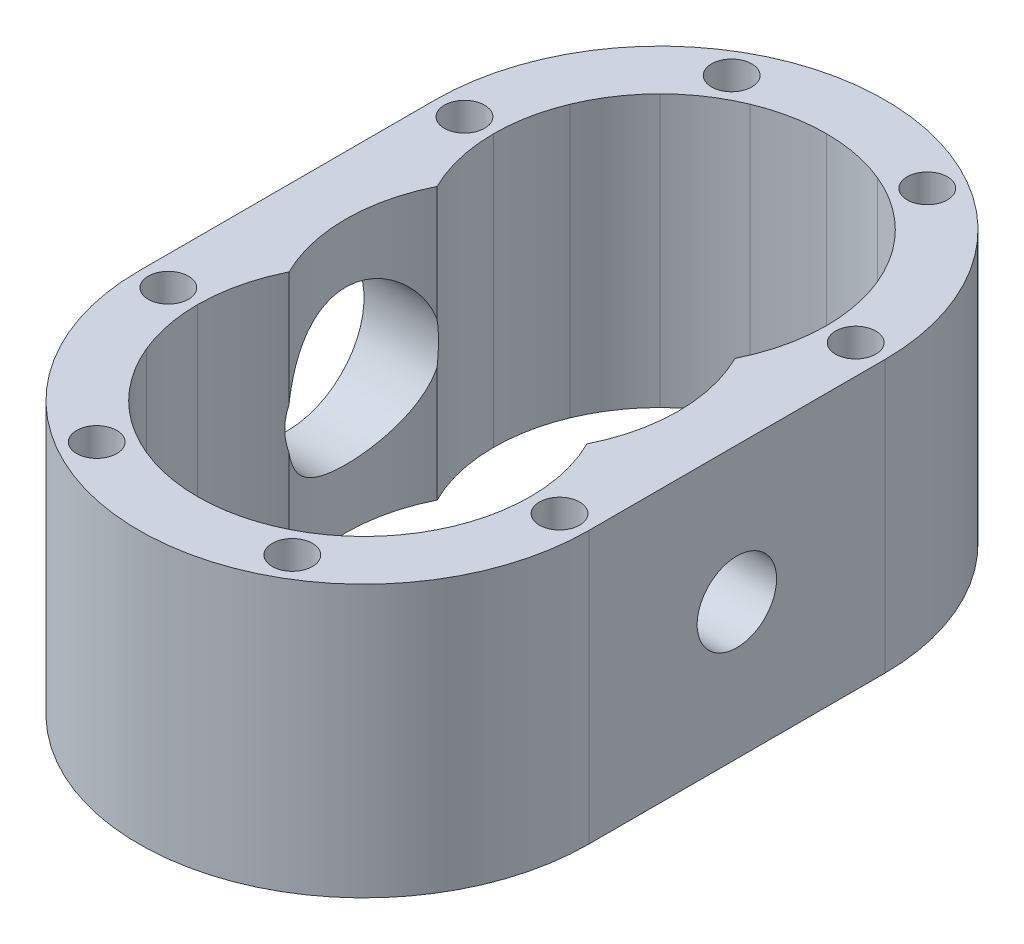
SolidWorks part; units mm, degrees
material "AISI 1020"
ref_plane "Ön Düzlem" through (0, 0, 0) normal (0, 0, 1) x (1, 0, 0)
ref_plane "Üst Düzlem" through (0, 0, 0) normal (0, 1, 0) x (1, 0, 0)
ref_plane "Sağ Düzlem" through (0, 0, 0) normal (1, 0, 0) x (0, 0, -1)
sketch "Çizim1" plane through (0, 0, 0) normal (0, 1, 0) x (1, 0, 0)
  line L0 (0, 40.5) -> (0, -40.5) construction
  line L1 (61.5, 40.5) -> (61.5, -40.5)
  line L2 (-61.5, 40.5) -> (-61.5, -40.5)
  arc A0 (61.5, 40.5) -> (-61.5, 40.5) centre (0, 40.5) ccw
  arc A1 (-61.5, -40.5) -> (61.5, -40.5) centre (0, -40.5) ccw
  point P3 (0, 0)
  dimension "D2" = 61.5
  dimension "D1" = 81
extrude "Yükseklik-Ekstrüzyon1" add sketch "Çizim1" along normal mid plane 74.3
sketch "Çizim2" plane through (0, 37.15, 0) normal (0, 1, 0) x (1, 0, 0)
  arc A0 (40.7454, 20.25) -> (-40.7454, 20.25) centre (0, 40.5) ccw
  arc A1 (-40.7454, -20.25) -> (40.7454, -20.25) centre (0, -40.5) ccw
  arc A2 (-40.7454, 20.25) -> (-40.7454, -20.25) centre (0, 0) ccw
  arc A3 (40.7454, -20.25) -> (40.7454, 20.25) centre (0, 0) ccw
  dimension "D1" = 91
extrude "Kes-Ekstrüzyon1" cut sketch "Çizim2" against normal up to surface (74.3 mm away) up to face at (0, -37.15, 0)
sketch "Çizim3" plane through (0, 37.15, 0) normal (0, 1, 0) x (1, 0, 0)
  line L0 (-45.5, 40.5) -> (-61.5, 40.5) construction
  line L1 (-61.5, 0) -> (61.5, 0) construction
  line L2 (-61.5, 40.5) -> (-61.5, -40.5) construction
  line L3 (61.5, -40.5) -> (61.5, 40.5) construction
  circle A0 centre (-53.5, 40.5) radius 5.5
  arc A1 (40.7454, 20.25) -> (-40.7454, 20.25) centre (0, 40.5) ccw construction
  dimension "D1" = 11
extrude "Kes-Ekstrüzyon2" cut sketch "Çizim3" against normal blind 12
pattern_circular "Dairesel Kaplama1" count 5 every 60 about axis through (0, 0, -40.5) along (0, 1, 0) of "Kes-Ekstrüzyon2"
mirror "Aynalama1" about plane through (0, 0, 0) normal (0, 0, 1) of "Dairesel Kaplama1", "Kes-Ekstrüzyon2"
mirror "Aynalama2" about plane through (0, 0, 0) normal (0, 1, 0) of "Dairesel Kaplama1", "Aynalama1", "Kes-Ekstrüzyon2"
sketch "Çizim4" plane through (-61.5, 0, 0) normal (-1, 0, 0) x (0, 0, 1)
  circle A0 centre (0, 0) radius 21.03
  dimension "D1" = 42.06
extrude "Kes-Ekstrüzyon3" cut sketch "Çizim4" against normal up to surface (21.1517 mm away)
sketch "Çizim5" plane through (61.5, 0, 0) normal (1, 0, 0) x (0, 0, -1)
  circle A0 centre (0, 0) radius 10.86
  dimension "D1" = 21.72
extrude "Kes-Ekstrüzyon4" cut sketch "Çizim5" against normal up to surface (17.315 mm away)
sketch "Çizim7" plane through (0, 0, 0) normal (1, 0, 0) x (0, 0, -1)
  line L0 (40.5, 37.15) -> (40.5, -37.15)
  line L1 (57.912, 37.15) -> (57.912, -37.15)
  line L2 (86, 37.15) -> (20.25, 37.15) construction
  line L3 (20.25, -37.15) -> (86, -37.15) construction
  line L4 (72.6734, 37.15) -> (72.6734, -37.15)
  line L5 (82.5365, 37.15) -> (82.5365, -37.15)
  line L6 (86, 37.15) -> (86, -37.15)
  line L7 (0, 40.865) -> (0, -40.865) construction
  line L8 (-86, 37.15) -> (-86, -37.15)
  line L9 (-82.5365, 37.15) -> (-82.5365, -37.15)
  line L10 (-72.6734, 37.15) -> (-72.6734, -37.15)
  line L11 (-57.912, 37.15) -> (-57.912, -37.15)
  line L12 (-40.5, 37.15) -> (-40.5, -37.15)
  dimension "D1" = 17.412
  dimension "D2" = 32.1734
  dimension "D3" = 42.0365
  dimension "D4" = 45.5
split line "Ayrım Çizgisi1"
equation "\"m\"= 5'modül"
equation "\"z\"= 16'diş sayısı"
equation "\"t\"= 16'cidar kalınlıgı"
equation "\"dt\"= \"m\" * \"z\"'taksimat d çapı"
equation "\"dg\"= 42.06'optimum giriş çapı"
equation "\"dç\"= 21.72'optimum çıkış çapı"
equation "\"ddıs\" = ( \"m\" * \"z\" + 2 * \"m\" + 1 ) / 2 + \"t\"'dış çap cidar dahil"
equation "\"b\" = \"m\" * 14.86'pompa genişliği"
equation "\"aks\"= \"m\" * \"z\" + 1'aks mesafesi"
equation "\"D1@Çizim1\"=\"aks\""
equation "\"D2@Çizim1\"=\"ddıs\""
equation "\"D1@Yükseklik-Ekstrüzyon1\"=\"b\""
equation "\"dk\"= \"m\" * \"z\" + 2 * \"m\"'diş tepesi çapı"
equation "\"D1@Çizim2\"=\"dk\"+1"
equation "\"ddelik\"= 11'delik çapı"
equation "\"Ldelik\"= 12'delik derinliği"
equation "\"D1@Kes-Ekstrüzyon2\"=\"Ldelik\""
equation "\"deliks\"= 4'yarım yüzdeki delik sayısı"
equation "\"D1@Çizim4\"=\"dg\""
equation "\"D1@Çizim5\"=\"dç\""
equation "\"D1@Çizim3\"=\"ddelik\""
